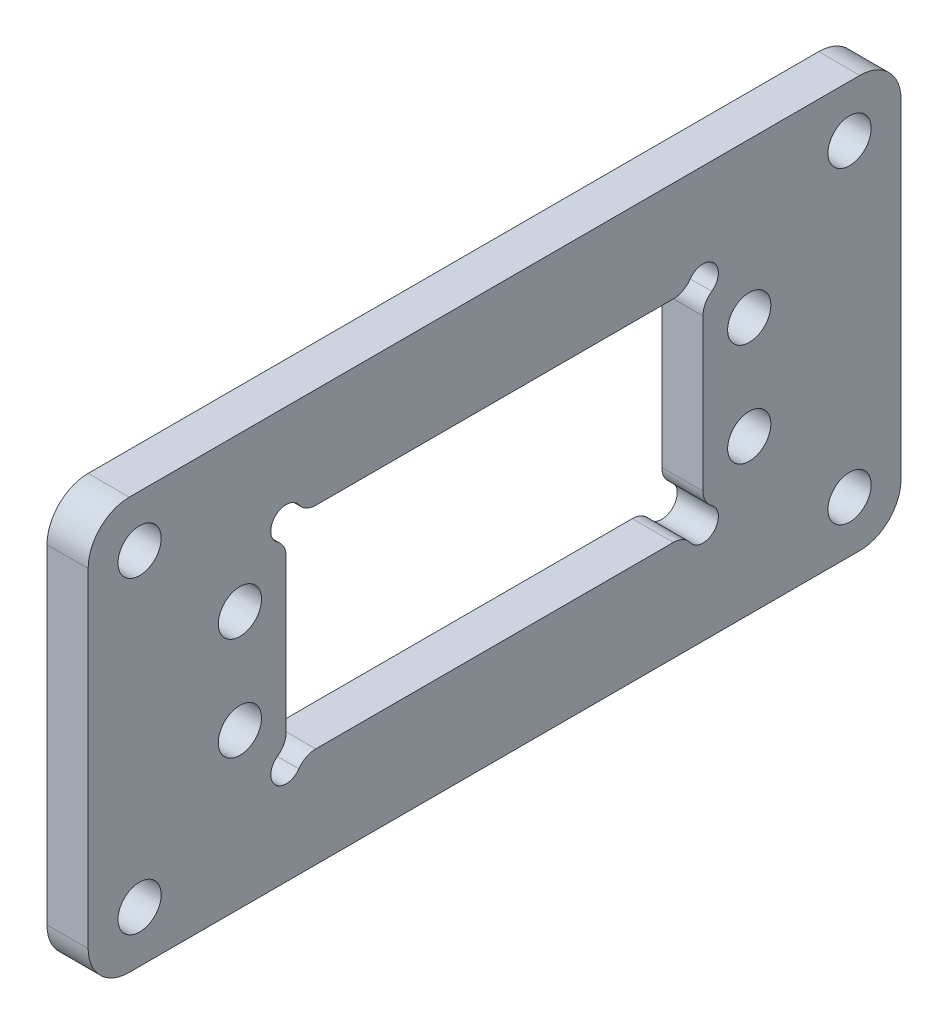
SolidWorks part; units mm, degrees
material "Thornel Mat VMA"
ref_plane "前视基准面" through (0, 0, 0) normal (0, 0, 1) x (1, 0, 0)
ref_plane "上视基准面" through (0, 0, 0) normal (0, 1, 0) x (1, 0, 0)
ref_plane "右视基准面" through (0, 0, 0) normal (1, 0, 0) x (0, 0, -1)
other "Configuration Table"
sketch "草图1" plane through (0, 0, 0) normal (1, 0, 0) x (0, 0, -1)
  line L1 (-39.5, -20) -> (39.5, -20)
  line L2 (-39.5, -20) -> (-39.5, 20)
  line L3 (-39.5, 20) -> (39.5, 20)
  line L4 (39.5, -20) -> (39.5, 20)
  line L5 (-39.5, -20) -> (39.5, 20) construction
  line L6 (-39.5, 20) -> (39.5, -20) construction
  line L7 (34.5, -15) -> (-34.5, -15) construction
  line L8 (34.5, -15) -> (34.5, 15) construction
  line L9 (34.5, 15) -> (-34.5, 15) construction
  line L10 (-34.5, -15) -> (-34.5, 15) construction
  line L11 (34.5, -15) -> (-34.5, 15) construction
  line L12 (34.5, 15) -> (-34.5, -15) construction
  line L13 (24.75, -5) -> (-24.75, -5) construction
  line L14 (24.75, -5) -> (24.75, 5) construction
  line L15 (24.75, 5) -> (-24.75, 5) construction
  line L16 (-24.75, -5) -> (-24.75, 5) construction
  line L17 (24.75, -5) -> (-24.75, 5) construction
  line L18 (24.75, 5) -> (-24.75, -5) construction
  line L19 (20.25, -10.25) -> (-20.25, -10.25)
  line L20 (20.25, -10.25) -> (20.25, 10.25)
  line L21 (20.25, 10.25) -> (-20.25, 10.25)
  line L22 (-20.25, -10.25) -> (-20.25, 10.25)
  line L23 (20.25, -10.25) -> (-20.25, 10.25) construction
  line L24 (20.25, 10.25) -> (-20.25, -10.25) construction
  circle A0 centre (-34.5, 15) radius 2.1
  circle A1 centre (-34.5, -15) radius 2.1
  circle A2 centre (-24.75, -5) radius 2.1
  circle A3 centre (-24.75, 5) radius 2.1
  circle A5 centre (24.75, 5) radius 2.1
  circle A6 centre (24.75, -5) radius 2.1
  circle A8 centre (34.5, 15) radius 2.1
  circle A9 centre (34.5, -15) radius 2.1
  point P0 (0, 0)
  point P5 (0, 0)
  point P11 (0, 0)
  point P16 (0, 0)
  dimension "D3" = 4.2
  dimension "D1" = 79
  dimension "D2" = 40
  dimension "D4" = 5
  dimension "D5" = 5
  dimension "D6" = 10
  dimension "D7" = 49.5
  dimension "D8" = 20.5
  dimension "D9" = 40.5
extrude "凸台-拉伸1" add sketch "草图1" along normal blind 4
fillet "圆角1" radius 4 4 edges at (2, -20, -39.5) (2, -20, 39.5) (2, 20, -39.5) (2, 20, 39.5)
sketch "草图2" plane through (4, 0, 0) normal (1, 0, 0) x (0, 0, -1)
  line L0 (20.25, -10.25) -> (20.25, 10.25) construction
  line L1 (20.25, 10.25) -> (-20.25, 10.25) construction
  circle A0 centre (-20.25, 10.25) radius 1.5
  circle A1 centre (-20.25, -10.25) radius 1.5
  circle A2 centre (20.25, -10.239) radius 1.5
  circle A3 centre (20.25, 10.25) radius 1.5
  dimension "D1" = 3
extrude "切除-拉伸1" cut sketch "草图2" against normal blind 10
fillet "圆角2" radius 2 8 edges at (2, 8.75, -20.25) (2, -8.739, -20.25) (2, -10.25, -18.75) (2, -10.25, 18.75) (2, -8.75, 20.25) (2, 8.75, 20.25) (2, 10.25, -18.75) (2, 10.25, 18.75)
